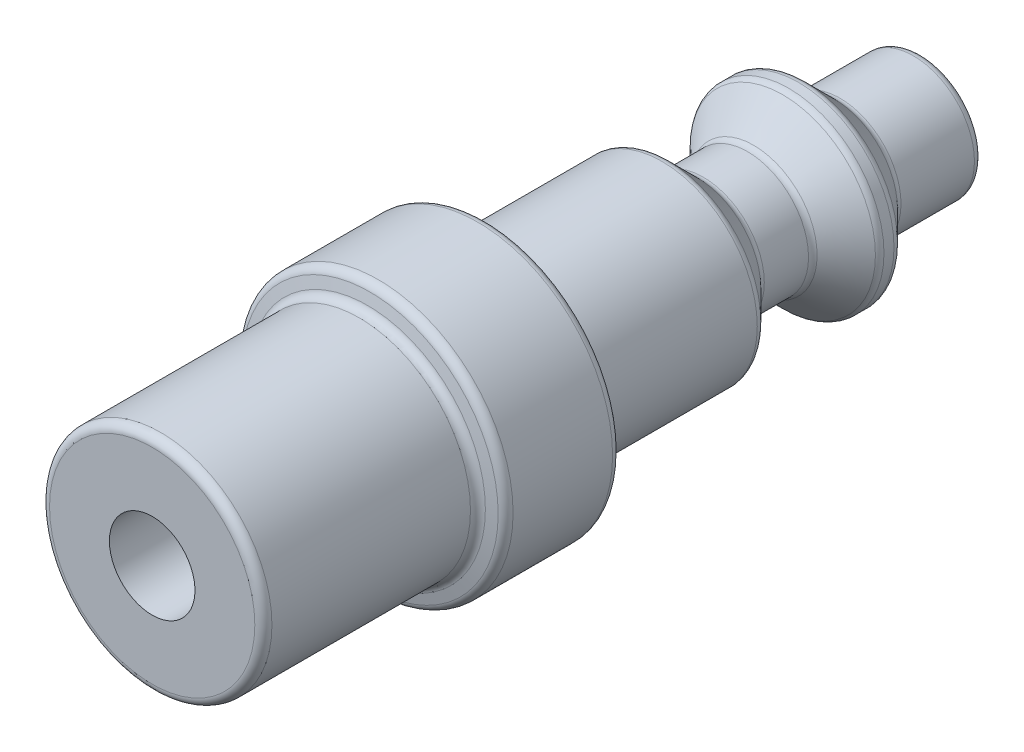
SolidWorks part; units mm, degrees
ref_plane "Front Plane" through (0, 0, 0) normal (0, 0, 1) x (1, 0, 0)
ref_plane "Top Plane" through (0, 0, 0) normal (0, 1, 0) x (1, 0, 0)
ref_plane "Right Plane" through (0, 0, 0) normal (1, 0, 0) x (0, 0, -1)
sketch "Sketch1" plane through (0, 0, 0) normal (0, 0, 1) x (1, 0, 0)
  circle A0 centre (0, 0) radius 7.875
  dimension "D1" = 15.75
extrude "Boss-Extrude1" add sketch "Sketch1" along normal blind 45
ref_axis "Axis1" through (0, 0, 45) along (0, 0, -1)
sketch "Sketch2" plane through (0, 0, 0) normal (0, 1, 0) x (1, 0, 0)
  line L0 (5.5637, -14.9874) -> (3.5637, -12.9916)
  line L1 (3.5637, 0) -> (17.2463, 0)
  line L2 (3.5637, -12.9916) -> (3.5637, -9.9916)
  line L3 (3.5637, -9.9916) -> (5.5637, -7.9958)
  line L4 (5.5637, -7.9958) -> (5.5637, -6.9958)
  line L5 (5.5637, -14.9874) -> (5.5637, -24.9874)
  line L6 (5.5637, -24.9874) -> (7.875, -25.5749)
  line L7 (7.875, -45) -> (7.875, 0) construction
  line L8 (7.875, -25.5749) -> (7.875, -32.1749)
  line L9 (7.875, -32.1749) -> (6.5, -32.5)
  line L10 (6.5, -32.5) -> (6.5, -45)
  line L11 (0, -45) -> (0, 0) construction
  line L12 (-7.875, -45) -> (7.875, -45) construction
  line L13 (5.5637, -6.9958) -> (3.5637, -5)
  line L14 (3.5637, -5) -> (3.5637, 0)
  line L15 (7.875, 0) -> (-7.875, 0) construction
  line L16 (17.2463, 0) -> (17.2463, -45)
  line L17 (17.2463, -45) -> (6.5, -45)
  point P21 (4.7, 0)
  point P22 (0, 0)
  point P23 (6.5, -24.7161)
  point P24 (5.285, -25.0228)
  point P27 (5.5637, -14.9874)
  dimension "D1" = 6.5
  dimension "D2" = 12.5
  dimension "D3" = 6.6
  dimension "D4" = 10
  dimension "D5" = 3
  dimension "D6" = 5
  dimension "D7" = 1
  dimension "D8" = 2
revolve "Cut-Revolve1" cut sketch "Sketch2" angle 360 about axis through (0, 0, 45) along (0, 0, -1)
sketch "Sketch3" plane through (0, 0, 0) normal (0, 0, -1) x (-1, 0, 0)
  circle A0 centre (0, 0) radius 2.5
  dimension "D1" = 5
extrude "Cut-Extrude1" cut sketch "Sketch3" against normal through all
fillet "Fillet1" radius 0.5 12 edges at (5.5637, 0, 7.9958) (5.5637, 0, 6.9958) (3.5637, 0, 5) (6.5, 0, 45) (6.5, 0, 32.5) (7.875, 0, 32.1749) (7.875, 0, 25.5749) (5.5637, 0, 24.9874) (5.5637, 0, 14.9874) (3.5637, 0, 12.9916) (3.5637, 0, 9.9916) (3.5637, 0, 0)
